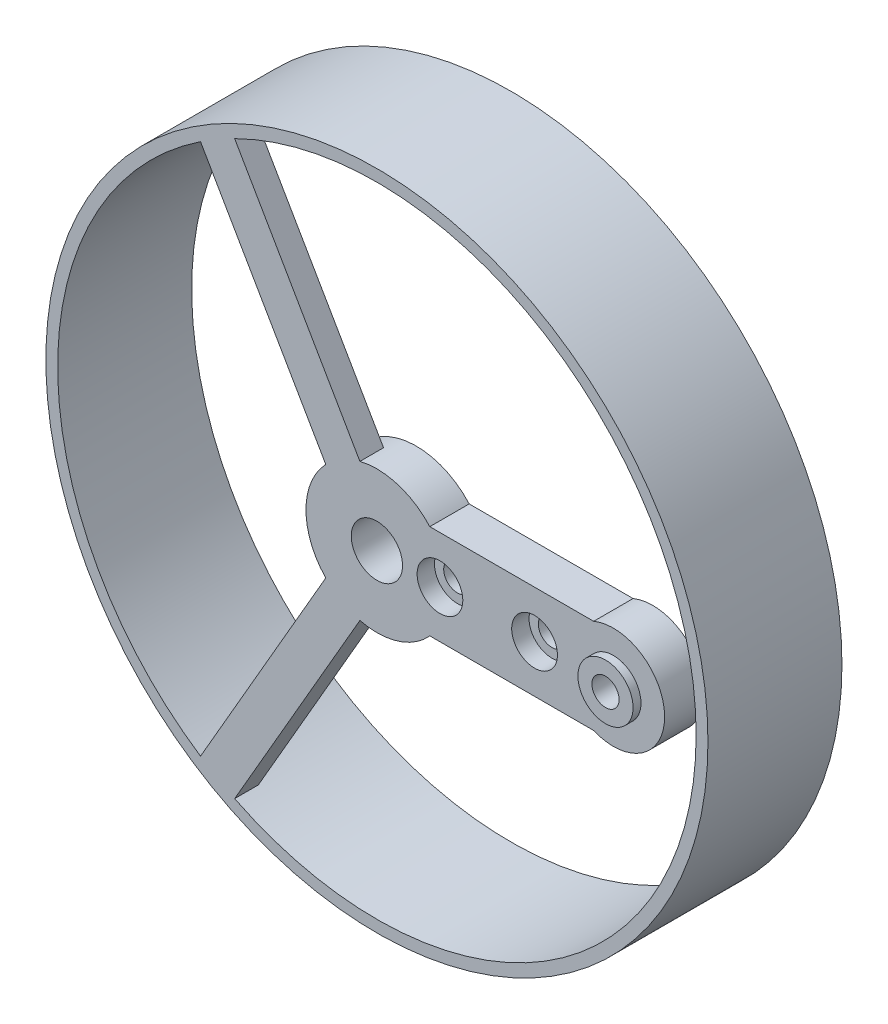
SolidWorks part; units mm, degrees
ref_plane "Front Plane" through (0, 0, 0) normal (0, 0, 1) x (1, 0, 0)
ref_plane "Top Plane" through (0, 0, 0) normal (0, 1, 0) x (1, 0, 0)
ref_plane "Right Plane" through (0, 0, 0) normal (1, 0, 0) x (0, 0, -1)
sketch "Sketch1" plane through (0, 0, 0) normal (0, 0, 1) x (1, 0, 0)
  line L0 (0, -6) -> (30, -6)
  line L1 (30, -6) -> (30, 6)
  line L2 (30, 6) -> (0, 6)
  line L3 (0, 6) -> (0, -6)
extrude "Boss-Extrude1" add sketch "Sketch1" along normal blind 5 from offset 9
sketch "Sketch2" plane through (0, 0, 0) normal (0, 0, 1) x (1, 0, 0)
  circle A0 centre (0, 0) radius 9
extrude "Boss-Extrude2" add sketch "Sketch2" along normal blind 5 from offset 9
sketch "Sketch3" plane through (0, 0, 0) normal (0, 0, 1) x (1, 0, 0)
  circle A0 centre (30, 0) radius 6.5
extrude "Boss-Extrude3" add sketch "Sketch3" along normal blind 5 from offset 9
sketch "Sketch4" plane through (0, 0, 0) normal (0, 0, 1) x (1, 0, 0)
  circle A0 centre (0, 0) radius 3.25
extrude "Cut-Extrude1" cut sketch "Sketch4" against normal through all and the other way through all
sketch "Sketch5" plane through (0, 0, 0) normal (0, 0, 1) x (1, 0, 0)
  circle A0 centre (8, 0) radius 1.725
  circle A1 centre (20, 0) radius 1.725
  circle A2 centre (30, 0) radius 1.725
extrude "Cut-Extrude2" cut sketch "Sketch5" against normal through all and the other way through all
sketch "Sketch6" plane through (0, 0, 0) normal (0, 0, 1) x (1, 0, 0)
  circle A0 centre (8, 0) radius 2.9
extrude "Cut-Extrude3" cut sketch "Sketch6" along normal blind 2.2 from offset 6.2
sketch "Sketch7" plane through (0, 0, 0) normal (0, 0, 1) x (1, 0, 0)
  circle A0 centre (20, 0) radius 2.9
extrude "Cut-Extrude4" cut sketch "Sketch7" along normal blind 2.2 from offset 6.2
sketch "Sketch8" plane through (0, 0, 0) normal (0, 0, 1) x (1, 0, 0)
  circle A0 centre (30, 0) radius 2.9
extrude "Cut-Extrude5" cut sketch "Sketch8" along normal blind 2.2 from offset 9
sketch "Sketch9" plane through (0, 0, 0) normal (0, 0, 1) x (1, 0, 0)
  circle A0 centre (30, 0) radius 3.5
extrude "Boss-Extrude4" add sketch "Sketch9" along normal blind 1 from offset 4
sketch "Sketch10" plane through (0, 0, 0) normal (0, 0, 1) x (1, 0, 0)
  circle A0 centre (30, 0) radius 1.725
extrude "Cut-Extrude6" cut sketch "Sketch10" against normal through all and the other way through all
sketch "Sketch11" plane through (0, 0, 0) normal (0, 0, 1) x (1, 0, 0)
  circle A0 centre (0, 0) radius 42
  circle A1 centre (0, 0) radius 40.5
extrude "Boss-Extrude5" add sketch "Sketch11" along normal blind 17 from offset 21
sketch "Sketch12" plane through (0, 0, 0) normal (0, 0, 1) x (1, 0, 0)
  line L0 (-1.3349, 7.3122) -> (-18.5849, 37.1901)
  line L1 (-18.5849, 37.1901) -> (-22.9151, 34.6901)
  line L2 (-22.9151, 34.6901) -> (-5.6651, 4.8122)
  line L3 (-5.6651, 4.8122) -> (-1.3349, 7.3122)
  line L4 (-5.6651, -4.8122) -> (-22.9151, -34.6901)
  line L5 (-22.9151, -34.6901) -> (-18.5849, -37.1901)
  line L6 (-18.5849, -37.1901) -> (-1.3349, -7.3122)
  line L7 (-1.3349, -7.3122) -> (-5.6651, -4.8122)
extrude "Boss-Extrude6" add sketch "Sketch12" along normal blind 3 from offset 7
